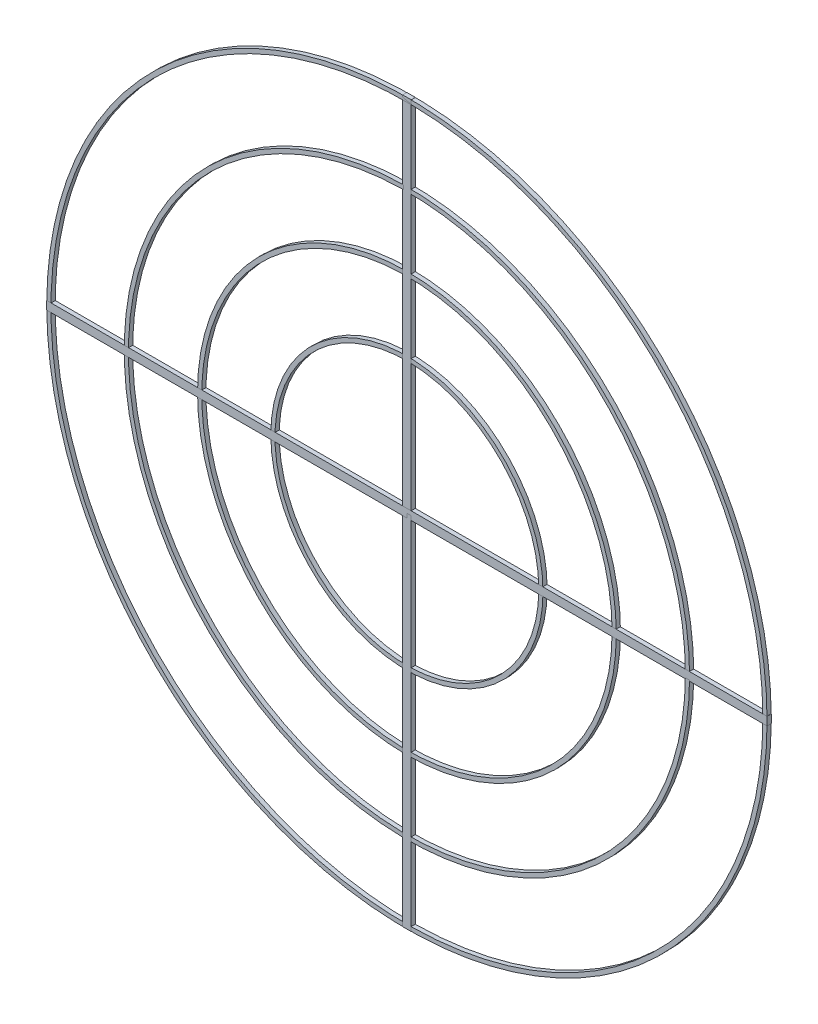
SolidWorks part; units mm, degrees
ref_plane "Front Plane" through (0, 0, 0) normal (0, 0, 1) x (1, 0, 0)
ref_plane "Top Plane" through (0, 0, 0) normal (0, 1, 0) x (1, 0, 0)
ref_plane "Right Plane" through (0, 0, 0) normal (1, 0, 0) x (0, 0, -1)
sketch "Sketch1" plane through (0, 0, 0) normal (0, 0, 1) x (1, 0, 0)
  circle A0 centre (0, 250) radius 65
  circle A1 centre (0, 250) radius 63
extrude "Guard_ring_ASSUMED" add sketch "Sketch1" along normal blind 2 from offset 450 separate body
sketch "Sketch2" plane through (0, 0, 0) normal (0, 0, 1) x (1, 0, 0)
  circle A0 centre (0, 250) radius 100
  circle A1 centre (0, 250) radius 98
extrude "Boss-Extrude2" add sketch "Sketch2" along normal blind 2 from offset 450 separate body
sketch "Sketch3" plane through (0, 0, 0) normal (0, 0, 1) x (1, 0, 0)
  circle A0 centre (0, 250) radius 135
  circle A1 centre (0, 250) radius 133
extrude "Boss-Extrude3" add sketch "Sketch3" along normal blind 2 from offset 450 separate body
sketch "Sketch4" plane through (0, 0, 0) normal (0, 0, 1) x (1, 0, 0)
  circle A0 centre (0, 250) radius 172
  circle A1 centre (0, 250) radius 170
extrude "Boss-Extrude4" add sketch "Sketch4" along normal blind 2 from offset 450 separate body
sketch "Sketch5" plane through (0, 0, 0) normal (0, 0, 1) x (1, 0, 0)
  line L1 (-172, 248) -> (172, 248)
  line L2 (-172, 248) -> (-172, 252)
  line L3 (-172, 252) -> (172, 252)
  line L4 (172, 248) -> (172, 252)
extrude "Guard_crossbar_horizontal" add sketch "Sketch5" along normal blind 2 from offset 450 separate body
sketch "Sketch6" plane through (0, 0, 0) normal (0, 0, 1) x (1, 0, 0)
  line L1 (-2, 78) -> (2, 78)
  line L2 (-2, 78) -> (-2, 422)
  line L3 (-2, 422) -> (2, 422)
  line L4 (2, 78) -> (2, 422)
extrude "Guard_crossbar_vertical" add sketch "Sketch6" along normal blind 2 from offset 450 separate body
